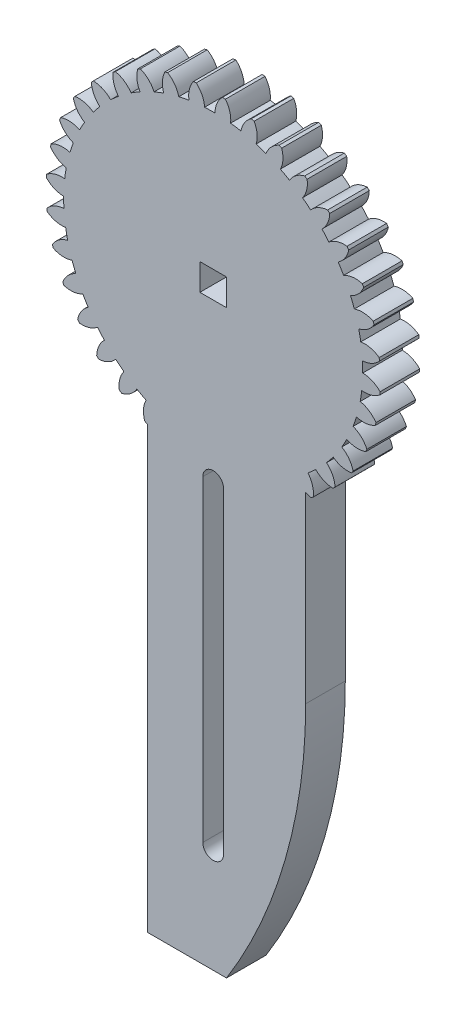
SolidWorks part; units mm, degrees
ref_plane "Front Plane" through (0, 0, 0) normal (0, 0, 1) x (1, 0, 0)
ref_plane "Top Plane" through (0, 0, 0) normal (0, 1, 0) x (1, 0, 0)
ref_plane "Right Plane" through (0, 0, 0) normal (1, 0, 0) x (0, 0, -1)
sketch "Sketch3" plane through (0, 0, 0) normal (0, 0, 1) x (1, 0, 0)
  line L1 (-1.6, -1.6) -> (1.6, -1.6)
  line L2 (-1.6, -1.6) -> (-1.6, 1.6)
  line L3 (-1.6, 1.6) -> (1.6, 1.6)
  line L4 (1.6, -1.6) -> (1.6, 1.6)
  line L5 (-1.6, -1.6) -> (1.6, 1.6) construction
  line L6 (-1.6, 1.6) -> (1.6, -1.6) construction
  line L16 (11.1252, -12.7) -> (11.1252, -38.1)
  line L18 (-7.9248, -12.7) -> (-7.9248, -71.4248)
  line L19 (-7.9248, -71.4248) -> (1.6002, -71.4248)
  line L21 (0, 0) -> (0, -12.7) construction
  line L22 (-7.9248, -12.7) -> (11.1252, -12.7)
  arc A0 (11.1252, -38.1) -> (1.6002, -71.4248) centre (-51.9335, -38.1) cw
  point P0 (0, 0)
  arc B0 (-16.8267, 6.3529) -> (-17.2288, 5.1637) centre (0, 0) ccw
  arc B1 (-17.9559, -1.0403) -> (-20.0006, -2.0372) centre (-17.7852, -3.9858) ccw
  arc B2 (-19.962, -2.3859) -> (-17.7488, -2.9115) centre (-18.2264, 0) ccw
  arc B3 (-17.7488, -2.9115) -> (-17.5024, -4.1425) centre (0, 0) ccw
  arc B4 (-17.8637, 2.0935) -> (-20.0505, 1.4668) centre (-18.2072, -0.8369) ccw
  arc B5 (-17.6742, 3.3345) -> (-17.8637, 2.0935) centre (0, 0) ccw
  arc B6 (-17.2288, 5.1637) -> (-19.4912, 4.9263) centre (-18.0759, 2.3374) ccw
  arc B7 (-19.5742, 4.5854) -> (-17.6742, 3.3345) centre (-17.1272, 6.2338) ccw
  arc B8 (-18.4806, 7.9147) -> (-16.8267, 6.3529) centre (-15.7845, 9.1132) ccw
  arc B9 (-13.6391, 11.7249) -> (-14.4237, 10.7449) centre (0, 0) ccw
  arc B10 (-14.6591, 13.7581) -> (-13.6391, 11.7249) centre (-11.7157, 13.9622) ccw
  arc B11 (-14.4167, 14.0119) -> (-14.6591, 13.7581) centre (0, 0) ccw
  arc B12 (-12.3388, 13.0863) -> (-14.4167, 14.0119) centre (-14.4855, 11.0622) ccw
  arc B13 (-11.3958, 13.9151) -> (-12.3388, 13.0863) centre (0, 0) ccw
  arc B14 (-12.0473, 16.0946) -> (-11.3958, 13.9151) centre (-9.1132, 15.7845) ccw
  arc B15 (-11.7646, 16.3024) -> (-12.0473, 16.0946) centre (0, 0) ccw
  arc B16 (-9.8789, 15.0301) -> (-11.7646, 16.3024) centre (-12.3444, 13.4095) ccw
  arc B17 (-8.8064, 15.6826) -> (-9.8789, 15.0301) centre (0, 0) ccw
  arc B18 (-9.0695, 17.9421) -> (-8.8064, 15.6826) centre (-6.2338, 17.1272) ccw
  arc B19 (-8.755, 18.0977) -> (-9.0695, 17.9421) centre (0, 0) ccw
  arc B20 (-7.1189, 16.5172) -> (-8.755, 18.0977) centre (-9.8284, 15.3494) ccw
  arc B21 (-5.9493, 16.9736) -> (-7.1189, 16.5172) centre (0, 0) ccw
  arc B22 (-5.8161, 19.2444) -> (-5.9493, 16.9736) centre (-3.165, 17.9495) ccw
  arc B23 (-5.4793, 19.343) -> (-5.8161, 19.2444) centre (0, 0) ccw
  arc B24 (-4.1425, 17.5024) -> (-5.4793, 19.343) centre (-7.0137, 16.8229) ccw
  arc B25 (-2.9115, 17.7488) -> (-4.1425, 17.5024) centre (0, 0) ccw
  arc B26 (-2.3859, 19.962) -> (-2.9115, 17.7488) centre (0, 18.2264) ccw
  arc B27 (-2.0372, 20.0006) -> (-2.3859, 19.962) centre (0, 0) ccw
  arc B28 (-1.0403, 17.9559) -> (-2.0372, 20.0006) centre (-3.9858, 17.7852) ccw
  arc B29 (0.2147, 17.9847) -> (-1.0403, 17.9559) centre (0, 0) ccw
  arc B30 (1.1167, 20.0731) -> (0.2147, 17.9847) centre (3.165, 17.9495) ccw
  arc B31 (1.4668, 20.0505) -> (1.1167, 20.0731) centre (0, 0) ccw
  arc B32 (2.0935, 17.8637) -> (1.4668, 20.0505) centre (-0.8369, 18.2072) ccw
  arc B33 (3.3345, 17.6742) -> (2.0935, 17.8637) centre (0, 0) ccw
  arc B34 (4.5854, 19.5742) -> (3.3345, 17.6742) centre (6.2338, 17.1272) ccw
  arc B35 (4.9263, 19.4912) -> (4.5854, 19.5742) centre (0, 0) ccw
  arc B36 (5.1637, 17.2288) -> (4.9263, 19.4912) centre (2.3374, 18.0759) ccw
  arc B37 (6.3529, 16.8267) -> (5.1637, 17.2288) centre (0, 0) ccw
  arc B38 (7.9147, 18.4806) -> (6.3529, 16.8267) centre (9.1132, 15.7845) ccw
  arc B39 (8.236, 18.3396) -> (7.9147, 18.4806) centre (0, 0) ccw
  arc B40 (8.077, 16.0704) -> (8.236, 18.3396) centre (5.4408, 17.3954) ccw
  arc B41 (9.1783, 15.4679) -> (8.077, 16.0704) centre (0, 0) ccw
  arc B42 (11.0036, 16.8254) -> (9.1783, 15.4679) centre (11.7157, 13.9622) ccw
  arc B43 (11.2956, 16.6308) -> (11.0036, 16.8254) centre (0, 0) ccw
  arc B44 (10.7449, 14.4237) -> (11.2956, 16.6308) centre (8.3788, 16.1863) ccw
  arc B45 (11.7249, 13.6391) -> (10.7449, 14.4237) centre (0, 0) ccw
  arc B46 (13.7581, 14.6591) -> (11.7249, 13.6391) centre (13.9622, 11.7157) ccw
  arc B47 (14.0119, 14.4167) -> (13.7581, 14.6591) centre (0, 0) ccw
  arc B48 (13.0863, 12.3388) -> (14.0119, 14.4167) centre (11.0622, 14.4855) ccw
  arc B49 (13.9151, 11.3958) -> (13.0863, 12.3388) centre (0, 0) ccw
  arc B50 (16.0946, 12.0473) -> (13.9151, 11.3958) centre (15.7845, 9.1132) ccw
  arc B51 (16.3024, 11.7646) -> (16.0946, 12.0473) centre (0, 0) ccw
  arc B52 (15.0301, 9.8789) -> (16.3024, 11.7646) centre (13.4095, 12.3444) ccw
  arc B53 (15.6826, 8.8064) -> (15.0301, 9.8789) centre (0, 0) ccw
  arc B54 (17.9421, 9.0695) -> (15.6826, 8.8064) centre (17.1272, 6.2338) ccw
  arc B55 (18.0977, 8.755) -> (17.9421, 9.0695) centre (0, 0) ccw
  arc B56 (16.5172, 7.1189) -> (18.0977, 8.755) centre (15.3494, 9.8284) ccw
  arc B57 (16.9736, 5.9493) -> (16.5172, 7.1189) centre (0, 0) ccw
  arc B58 (19.2444, 5.8161) -> (16.9736, 5.9493) centre (17.9495, 3.165) ccw
  arc B59 (19.343, 5.4793) -> (19.2444, 5.8161) centre (0, 0) ccw
  arc B60 (17.5024, 4.1425) -> (19.343, 5.4793) centre (16.8229, 7.0137) ccw
  arc B61 (17.7488, 2.9115) -> (17.5024, 4.1425) centre (0, 0) ccw
  arc B62 (19.962, 2.3859) -> (17.7488, 2.9115) centre (18.2264, 0) ccw
  arc B63 (20.0006, 2.0372) -> (19.962, 2.3859) centre (0, 0) ccw
  arc B64 (17.9559, 1.0403) -> (20.0006, 2.0372) centre (17.7852, 3.9858) ccw
  arc B65 (17.9847, -0.2147) -> (17.9559, 1.0403) centre (0, 0) ccw
  arc B66 (20.0731, -1.1167) -> (17.9847, -0.2147) centre (17.9495, -3.165) ccw
  arc B67 (20.0505, -1.4668) -> (20.0731, -1.1167) centre (0, 0) ccw
  arc B68 (17.8637, -2.0935) -> (20.0505, -1.4668) centre (18.2072, 0.8369) ccw
  arc B69 (17.6742, -3.3345) -> (17.8637, -2.0935) centre (0, 0) ccw
  arc B70 (19.5742, -4.5854) -> (17.6742, -3.3345) centre (17.1272, -6.2338) ccw
  arc B71 (19.4912, -4.9263) -> (19.5742, -4.5854) centre (0, 0) ccw
  arc B72 (17.2288, -5.1637) -> (19.4912, -4.9263) centre (18.0759, -2.3374) ccw
  arc B73 (16.8267, -6.3529) -> (17.2288, -5.1637) centre (0, 0) ccw
  arc B74 (18.4806, -7.9147) -> (16.8267, -6.3529) centre (15.7845, -9.1132) ccw
  arc B75 (18.3396, -8.236) -> (18.4806, -7.9147) centre (0, 0) ccw
  arc B76 (16.0704, -8.077) -> (18.3396, -8.236) centre (17.3954, -5.4408) ccw
  arc B77 (15.4679, -9.1783) -> (16.0704, -8.077) centre (0, 0) ccw
  arc B78 (16.8254, -11.0036) -> (15.4679, -9.1783) centre (13.9622, -11.7157) ccw
  arc B79 (16.6308, -11.2956) -> (16.8254, -11.0036) centre (0, 0) ccw
  arc B80 (14.4237, -10.7449) -> (16.6308, -11.2956) centre (16.1863, -8.3788) ccw
  arc B81 (13.6391, -11.7249) -> (14.4237, -10.7449) centre (0, 0) ccw
  arc B82 (14.6591, -13.7581) -> (13.6391, -11.7249) centre (11.7157, -13.9622) ccw
  arc B83 (14.4167, -14.0119) -> (14.6591, -13.7581) centre (0, 0) ccw
  arc B84 (12.3388, -13.0863) -> (14.4167, -14.0119) centre (14.4855, -11.0622) ccw
  arc B85 (11.3958, -13.9151) -> (12.3388, -13.0863) centre (0, 0) ccw
  arc B86 (12.0473, -16.0946) -> (11.3958, -13.9151) centre (9.1132, -15.7845) ccw
  arc B87 (11.7646, -16.3024) -> (12.0473, -16.0946) centre (0, 0) ccw
  arc B88 (9.8789, -15.0301) -> (11.7646, -16.3024) centre (12.3444, -13.4095) ccw
  arc B89 (8.8064, -15.6826) -> (9.8789, -15.0301) centre (0, 0) ccw
  arc B90 (9.0695, -17.9421) -> (8.8064, -15.6826) centre (6.2338, -17.1272) ccw
  arc B91 (8.755, -18.0977) -> (9.0695, -17.9421) centre (0, 0) ccw
  arc B92 (7.1189, -16.5172) -> (8.755, -18.0977) centre (9.8284, -15.3494) ccw
  arc B93 (5.9493, -16.9736) -> (7.1189, -16.5172) centre (0, 0) ccw
  arc B94 (5.8161, -19.2444) -> (5.9493, -16.9736) centre (3.165, -17.9495) ccw
  arc B95 (5.4793, -19.343) -> (5.8161, -19.2444) centre (0, 0) ccw
  arc B96 (4.1425, -17.5024) -> (5.4793, -19.343) centre (7.0137, -16.8229) ccw
  arc B97 (2.9115, -17.7488) -> (4.1425, -17.5024) centre (0, 0) ccw
  arc B98 (2.3859, -19.962) -> (2.9115, -17.7488) centre (0, -18.2264) ccw
  arc B99 (2.0372, -20.0006) -> (2.3859, -19.962) centre (0, 0) ccw
  arc B100 (1.0403, -17.9559) -> (2.0372, -20.0006) centre (3.9858, -17.7852) ccw
  arc B101 (-0.2147, -17.9847) -> (1.0403, -17.9559) centre (0, 0) ccw
  arc B102 (-1.1167, -20.0731) -> (-0.2147, -17.9847) centre (-3.165, -17.9495) ccw
  arc B103 (-1.4668, -20.0505) -> (-1.1167, -20.0731) centre (0, 0) ccw
  arc B104 (-2.0935, -17.8637) -> (-1.4668, -20.0505) centre (0.8369, -18.2072) ccw
  arc B105 (-3.3345, -17.6742) -> (-2.0935, -17.8637) centre (0, 0) ccw
  arc B106 (-4.5854, -19.5742) -> (-3.3345, -17.6742) centre (-6.2338, -17.1272) ccw
  arc B107 (-4.9263, -19.4912) -> (-4.5854, -19.5742) centre (0, 0) ccw
  arc B108 (-5.1637, -17.2288) -> (-4.9263, -19.4912) centre (-2.3374, -18.0759) ccw
  arc B109 (-6.3529, -16.8267) -> (-5.1637, -17.2288) centre (0, 0) ccw
  arc B110 (-7.9147, -18.4806) -> (-6.3529, -16.8267) centre (-9.1132, -15.7845) ccw
  arc B111 (-8.236, -18.3396) -> (-7.9147, -18.4806) centre (0, 0) ccw
  arc B112 (-8.077, -16.0704) -> (-8.236, -18.3396) centre (-5.4408, -17.3954) ccw
  arc B113 (-9.1783, -15.4679) -> (-8.077, -16.0704) centre (0, 0) ccw
  arc B114 (-11.0036, -16.8254) -> (-9.1783, -15.4679) centre (-11.7157, -13.9622) ccw
  arc B115 (-11.2956, -16.6308) -> (-11.0036, -16.8254) centre (0, 0) ccw
  arc B116 (-10.7449, -14.4237) -> (-11.2956, -16.6308) centre (-8.3788, -16.1863) ccw
  arc B117 (-11.7249, -13.6391) -> (-10.7449, -14.4237) centre (0, 0) ccw
  arc B118 (-13.7581, -14.6591) -> (-11.7249, -13.6391) centre (-13.9622, -11.7157) ccw
  arc B119 (-14.0119, -14.4167) -> (-13.7581, -14.6591) centre (0, 0) ccw
  arc B120 (-13.0863, -12.3388) -> (-14.0119, -14.4167) centre (-11.0622, -14.4855) ccw
  arc B121 (-13.9151, -11.3958) -> (-13.0863, -12.3388) centre (0, 0) ccw
  arc B122 (-16.0946, -12.0473) -> (-13.9151, -11.3958) centre (-15.7845, -9.1132) ccw
  arc B123 (-16.3024, -11.7646) -> (-16.0946, -12.0473) centre (0, 0) ccw
  arc B124 (-15.0301, -9.8789) -> (-16.3024, -11.7646) centre (-13.4095, -12.3444) ccw
  arc B125 (-15.6826, -8.8064) -> (-15.0301, -9.8789) centre (0, 0) ccw
  arc B126 (-17.9421, -9.0695) -> (-15.6826, -8.8064) centre (-17.1272, -6.2338) ccw
  arc B127 (-18.0977, -8.755) -> (-17.9421, -9.0695) centre (0, 0) ccw
  arc B128 (-16.5172, -7.1189) -> (-18.0977, -8.755) centre (-15.3494, -9.8284) ccw
  arc B129 (-16.9736, -5.9493) -> (-16.5172, -7.1189) centre (0, 0) ccw
  arc B130 (-19.2444, -5.8161) -> (-16.9736, -5.9493) centre (-17.9495, -3.165) ccw
  arc B131 (-19.343, -5.4793) -> (-19.2444, -5.8161) centre (0, 0) ccw
  arc B132 (-17.5024, -4.1425) -> (-19.343, -5.4793) centre (-16.8229, -7.0137) ccw
  arc B133 (-20.0006, -2.0372) -> (-19.962, -2.3859) centre (0, 0) ccw
  arc B134 (-17.9847, 0.2147) -> (-17.9559, -1.0403) centre (0, 0) ccw
  arc B135 (-20.0731, 1.1167) -> (-17.9847, 0.2147) centre (-17.9495, 3.165) ccw
  arc B136 (-20.0505, 1.4668) -> (-20.0731, 1.1167) centre (0, 0) ccw
  arc B137 (-19.4912, 4.9263) -> (-19.5742, 4.5854) centre (0, 0) ccw
  arc B138 (-18.3396, 8.236) -> (-18.4806, 7.9147) centre (0, 0) ccw
  arc B139 (-16.0704, 8.077) -> (-18.3396, 8.236) centre (-17.3954, 5.4408) ccw
  arc B140 (-15.4679, 9.1783) -> (-16.0704, 8.077) centre (0, 0) ccw
  arc B141 (-16.8254, 11.0036) -> (-15.4679, 9.1783) centre (-13.9622, 11.7157) ccw
  arc B142 (-16.6308, 11.2956) -> (-16.8254, 11.0036) centre (0, 0) ccw
  arc B143 (-14.4237, 10.7449) -> (-16.6308, 11.2956) centre (-16.1863, 8.3788) ccw
sketch_block_instance "VEX-36-TOOTH-GEAR-b-1"
sketch_block "VEX-36-TOOTH-GEAR-b"
other "DetailItem3"
other "DetailItem4" parameters "D3"=5.08, "D2"=55.88, "D7"=68.7917, "D1"=3.0671, "D4"=22.6056, "D5"=9.525, "D6"=19.05
extrude "Boss-Extrude2" add sketch "Sketch3" along normal blind 4.7625
sketch "Sketch4" plane through (0, 0, 4.7625) normal (0, 0, 1) x (1, 0, 0)
  circle A0 centre (0, 0) radius 2.2627
sketch "Sketch5" plane through (0, 0, 4.7625) normal (0, 0, 1) x (1, 0, 0)
  line L0 (0, -58.7248) -> (0, -20.6248) construction
  line L1 (-1.25, -58.7248) -> (-1.25, -20.6248)
  line L2 (1.25, -58.7248) -> (1.25, -20.6248)
  line L3 (-7.9248, -71.4248) -> (1.6002, -71.4248) construction
  arc A0 (-1.25, -58.7248) -> (1.25, -58.7248) centre (0, -58.7248) ccw
  arc A1 (1.25, -20.6248) -> (-1.25, -20.6248) centre (0, -20.6248) ccw
  point P3 (0, -39.6748)
  dimension "D1" = 2.5
  dimension "D2" = 38.1
  dimension "D3" = 12.7
extrude "Cut-Extrude1" cut sketch "Sketch5" against normal through all
equation "\"DIST\"= 0"
